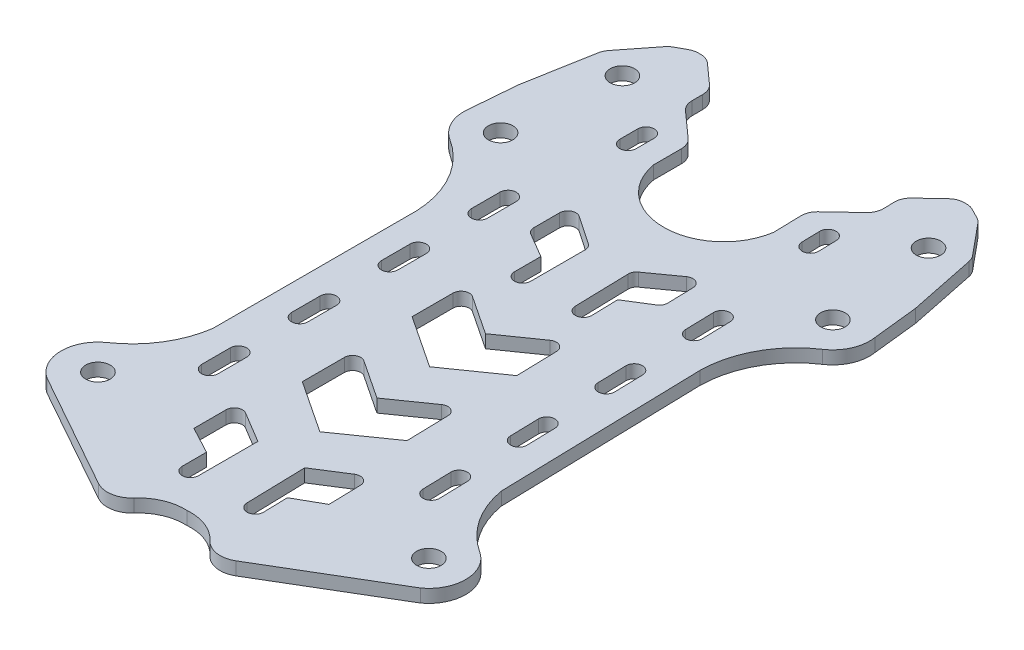
SolidWorks part; units mm, degrees
material "Thornel Mat VMA"
ref_plane "Front Plane" through (0, 0, 0) normal (0, 0, 1) x (1, 0, 0)
ref_plane "Top Plane" through (0, 0, 0) normal (0, 1, 0) x (1, 0, 0)
ref_plane "Right Plane" through (0, 0, 0) normal (1, 0, 0) x (0, 0, -1)
sketch "Sketch1" plane through (0, 0, 0) normal (0, 1, 0) x (1, 0, 0)
  line L0 (480.3423, 413.9052) -> (480.3423, 495.9052) construction
  line L1 (467.9459, 415.8441) -> (453.5897, 423.8818)
  line L2 (458.5115, 439.2435) -> (458.5115, 464.1937)
  line L3 (450.9298, 478.2127) -> (451.3961, 483.794)
  line L4 (451.3961, 483.794) -> (452.8757, 492.0554)
  line L5 (453.2719, 492.9386) -> (456.2786, 496.7643)
  line L6 (456.8868, 497.2807) -> (458.0612, 497.927)
  line L7 (459.0255, 498.1748) -> (459.3166, 498.1748)
  line L8 (460.6508, 497.6647) -> (463.0319, 495.5325)
  line L9 (463.6977, 494.0426) -> (463.6977, 492.7589)
  line L10 (464.3635, 491.2689) -> (467.4781, 488.4799)
  line L11 (468.1439, 486.99) -> (468.1439, 483.5933)
  line L12 (476.2276, 418.3953) -> (475.7559, 455.3953) construction
  line L13 (462.636, 471.2797) -> (462.636, 467.7797) construction
  line L14 (463.636, 471.2797) -> (463.636, 467.7797)
  line L15 (461.636, 471.2797) -> (461.636, 467.7797)
  line L16 (462.636, 460.2797) -> (462.636, 456.7797) construction
  line L19 (462.636, 469.5297) -> (462.636, 436.5297) construction
  line L20 (463.636, 460.2797) -> (463.636, 456.7797)
  line L21 (461.636, 460.2797) -> (461.636, 456.7797)
  line L22 (462.636, 449.2797) -> (462.636, 445.7797) construction
  line L23 (463.636, 449.2797) -> (463.636, 445.7797)
  line L24 (461.636, 449.2797) -> (461.636, 445.7797)
  line L25 (462.636, 438.2797) -> (462.636, 434.7797) construction
  line L28 (463.636, 438.2797) -> (463.636, 434.7797)
  line L29 (461.636, 438.2797) -> (461.636, 434.7797)
  line L30 (475.7559, 455.3953) -> (475.4729, 477.591) construction
  line L31 (472.9659, 463.7324) -> (472.9659, 470.3809)
  line L32 (472.5276, 471.2082) -> (469.0398, 473.5761)
  line L33 (467.4781, 472.7487) -> (467.4781, 469.5911)
  line L34 (467.9703, 468.7297) -> (470.9659, 466.9637)
  line L35 (470.9659, 466.9637) -> (470.9659, 463.7324)
  line L36 (464.3635, 486.4313) -> (464.3635, 484.2313) construction
  line L37 (465.3635, 486.4313) -> (465.3635, 484.2313)
  line L38 (463.3635, 486.4313) -> (463.3635, 484.2313)
  line L39 (475.7559, 455.3953) -> (471.0157, 458.5408)
  line L40 (469.4627, 457.7076) -> (469.4627, 452.706)
  line L41 (469.4627, 452.706) -> (475.8442, 448.4714)
  line L42 (475.9275, 441.9373) -> (471.188, 445.0823)
  line L43 (469.6351, 444.2491) -> (469.6351, 439.1023)
  line L44 (469.6351, 439.1023) -> (476.0176, 434.8669)
  line L45 (473.247, 430.0492) -> (469.4602, 432.3204)
  line L46 (467.9459, 431.4628) -> (467.9459, 427.5216)
  line L47 (467.9459, 427.5216) -> (471.247, 425.7613)
  line L48 (471.247, 425.7613) -> (471.247, 422.7871)
  line L49 (473.247, 430.0492) -> (473.247, 422.7749)
  line L50 (488.5111, 469.8596) -> (489.3525, 436.8703) construction
  line L51 (478.9102, 430.1214) -> (479.0957, 422.8495)
  line L52 (481.0188, 425.8859) -> (481.0946, 422.9127)
  line L53 (484.274, 427.7298) -> (481.0188, 425.8859)
  line L54 (484.1735, 431.6697) -> (484.274, 427.7298)
  line L55 (478.9102, 430.1214) -> (482.6378, 432.4884)
  line L56 (482.2901, 439.2636) -> (476.0176, 434.8669)
  line L57 (482.1589, 444.4088) -> (482.2901, 439.2636)
  line L58 (475.9275, 441.9373) -> (480.5852, 445.2021)
  line L59 (482.1155, 452.8673) -> (475.8442, 448.4714)
  line L60 (481.988, 457.8673) -> (482.1155, 452.8673)
  line L61 (475.7559, 455.3953) -> (480.4143, 458.6607)
  line L62 (480.2493, 467.0821) -> (480.3317, 463.8518)
  line L63 (483.1989, 468.9238) -> (480.2493, 467.0821)
  line L64 (483.5885, 472.9541) -> (483.669, 469.7976)
  line L65 (478.5799, 471.2854) -> (482.0062, 473.7414)
  line L66 (478.3324, 463.8008) -> (478.1628, 470.4471)
  line L67 (482.5598, 487.1738) -> (482.6464, 483.7782)
  line L68 (486.2298, 491.5477) -> (483.1874, 488.6802)
  line L69 (486.8247, 494.3375) -> (486.8574, 493.0542)
  line L70 (489.7783, 498.0361) -> (487.4523, 495.8439)
  line L71 (491.3901, 498.5874) -> (491.099, 498.58)
  line L72 (493.5508, 497.7482) -> (492.3603, 498.3643)
  line L73 (497.2753, 493.4997) -> (494.172, 497.2475)
  line L74 (499.3836, 484.4059) -> (497.6939, 492.6268)
  line L75 (499.992, 478.8383) -> (499.3836, 484.4059)
  line L76 (493.4065, 439.6885) -> (492.7703, 464.6305)
  line L77 (484.5718, 416.0561) -> (498.7183, 424.4572)
  line L78 (486.3532, 486.7117) -> (486.4093, 484.5124) construction
  line L79 (485.3535, 486.6862) -> (485.4096, 484.4869)
  line L80 (487.3529, 486.7372) -> (487.4089, 484.5379)
  line L81 (489.3079, 438.6198) -> (489.3972, 435.1209) construction
  line L82 (488.3082, 438.5943) -> (488.3975, 435.0954)
  line L83 (490.3076, 438.6452) -> (490.3968, 435.1464)
  line L84 (489.0274, 449.6162) -> (489.1167, 446.1173) construction
  line L85 (488.0278, 449.5907) -> (488.117, 446.0918)
  line L86 (490.0271, 449.6417) -> (490.1164, 446.1428)
  line L87 (488.747, 460.6126) -> (488.8362, 457.1137) construction
  line L88 (487.7473, 460.5871) -> (487.8365, 457.0882)
  line L89 (489.7467, 460.6381) -> (489.8359, 457.1392)
  line L90 (488.4665, 471.609) -> (488.5558, 468.1102) construction
  line L91 (487.4668, 471.5835) -> (487.5561, 468.0847)
  line L92 (489.4662, 471.6345) -> (489.5554, 468.1357)
  line L93 (456.799, 491.1108) -> (493.796, 491.5826) construction
  circle A0 centre (455.3894, 477.6108) radius 1.5
  arc A1 (450.9298, 478.2127) -> (452.9867, 473.806) centre (455.3894, 477.6108) ccw
  circle A2 centre (456.1085, 427.6108) radius 1.5
  arc A3 (453.5654, 431.3233) -> (453.5897, 423.8818) centre (456.1085, 427.6108) ccw
  arc A4 (453.5654, 431.3233) -> (458.5115, 439.2435) centre (446.9757, 440.943) ccw
  arc A5 (458.5115, 464.1937) -> (452.9867, 473.806) centre (446.6487, 463.7692) ccw
  arc A6 (468.1439, 483.5933) -> (475.4729, 477.591) centre (475.2975, 484.8524) ccw
  circle A7 centre (456.799, 491.1108) radius 1.5
  arc A8 (476.2276, 418.3953) -> (471.6613, 416.4773) centre (475.9279, 412.7141) ccw
  arc A9 (467.9459, 415.8441) -> (471.6613, 416.4773) centre (469.4114, 418.4617) ccw
  arc A10 (467.4781, 488.4799) -> (468.1439, 486.99) centre (466.1439, 486.99) cw
  arc A11 (463.6977, 492.7589) -> (464.3635, 491.2689) centre (465.6977, 492.7589) ccw
  arc A12 (463.0319, 495.5325) -> (463.6977, 494.0426) centre (461.6977, 494.0426) cw
  arc A13 (459.3166, 498.1748) -> (460.6508, 497.6647) centre (459.3166, 496.1748) cw
  arc A14 (458.0612, 497.927) -> (459.0255, 498.1748) centre (459.0255, 496.1748) cw
  arc A15 (456.2786, 496.7643) -> (456.8868, 497.2807) centre (457.8511, 495.5285) cw
  arc A16 (452.8757, 492.0554) -> (453.2719, 492.9386) centre (454.8444, 491.7028) cw
  arc A17 (463.636, 471.2797) -> (461.636, 471.2797) centre (462.636, 471.2797) ccw
  arc A18 (461.636, 467.7797) -> (463.636, 467.7797) centre (462.636, 467.7797) ccw
  arc A19 (463.636, 460.2797) -> (461.636, 460.2797) centre (462.636, 460.2797) ccw
  arc A20 (461.636, 456.7797) -> (463.636, 456.7797) centre (462.636, 456.7797) ccw
  arc A21 (463.636, 449.2797) -> (461.636, 449.2797) centre (462.636, 449.2797) ccw
  arc A22 (461.636, 445.7797) -> (463.636, 445.7797) centre (462.636, 445.7797) ccw
  arc A25 (463.636, 438.2797) -> (461.636, 438.2797) centre (462.636, 438.2797) ccw
  arc A26 (461.636, 434.7797) -> (463.636, 434.7797) centre (462.636, 434.7797) ccw
  arc A27 (470.9659, 463.7324) -> (472.9659, 463.7324) centre (471.9659, 463.7324) ccw
  arc A28 (469.0398, 473.5761) -> (467.4781, 472.7487) centre (468.4781, 472.7487) ccw
  arc A29 (467.4781, 469.5911) -> (467.9703, 468.7297) centre (468.4781, 469.5911) ccw
  arc A30 (472.9659, 470.3809) -> (472.5276, 471.2082) centre (471.9659, 470.3809) ccw
  arc A31 (465.3635, 486.4313) -> (463.3635, 486.4313) centre (464.3635, 486.4313) ccw
  arc A32 (463.3635, 484.2313) -> (465.3635, 484.2313) centre (464.3635, 484.2313) ccw
  arc A33 (471.0157, 458.5408) -> (469.4627, 457.7076) centre (470.4627, 457.7076) ccw
  arc A34 (471.188, 445.0823) -> (469.6351, 444.2491) centre (470.6351, 444.2491) ccw
  arc A35 (471.247, 422.7871) -> (473.247, 422.7993) centre (472.247, 422.7871) ccw
  arc A36 (469.4602, 432.3204) -> (467.9459, 431.4628) centre (468.9459, 431.4628) ccw
  arc A37 (482.6378, 432.4884) -> (484.1735, 431.6697) centre (483.1739, 431.6442) cw
  arc A38 (481.0946, 422.9127) -> (479.095, 422.8738) centre (480.095, 422.8872) cw
  arc A39 (480.5852, 445.2021) -> (482.1589, 444.4088) centre (481.1592, 444.3833) cw
  arc A40 (480.4143, 458.6607) -> (481.988, 457.8673) centre (480.9883, 457.8418) cw
  arc A41 (478.1628, 470.4471) -> (478.5799, 471.2854) centre (479.1625, 470.4726) cw
  arc A42 (483.669, 469.7976) -> (483.1989, 468.9238) centre (482.6693, 469.7721) cw
  arc A43 (482.0062, 473.7414) -> (483.5885, 472.9541) centre (482.5888, 472.9286) cw
  arc A44 (480.3317, 463.8518) -> (478.3324, 463.8008) centre (479.332, 463.8263) cw
  arc A45 (497.6939, 492.6268) -> (497.2753, 493.4997) centre (495.7348, 492.2242) ccw
  arc A46 (494.172, 497.2475) -> (493.5508, 497.7482) centre (492.6315, 495.9719) ccw
  arc A47 (492.3603, 498.3643) -> (491.3901, 498.5874) centre (491.4411, 496.5881) ccw
  arc A48 (491.099, 498.58) -> (489.7783, 498.0361) centre (491.15, 496.5807) ccw
  arc A49 (487.4523, 495.8439) -> (486.8247, 494.3375) centre (488.8241, 494.3885) ccw
  arc A50 (486.8574, 493.0542) -> (486.2298, 491.5477) centre (484.8581, 493.0032) cw
  arc A51 (483.1874, 488.6802) -> (482.5598, 487.1738) centre (484.5591, 487.2248) ccw
  arc A52 (484.5718, 416.0561) -> (480.8414, 416.5944) centre (483.0399, 418.6355) cw
  arc A53 (476.2276, 418.3953) -> (480.8414, 416.5944) centre (476.6721, 412.7236) cw
  circle A54 centre (493.796, 491.5826) radius 1.5
  arc A55 (482.6464, 483.7782) -> (475.4729, 477.591) centre (475.4631, 484.8545) cw
  arc A56 (492.7703, 464.6305) -> (498.0482, 474.3805) centre (504.6401, 464.5087) cw
  arc A57 (498.5529, 431.8969) -> (493.4065, 439.6885) centre (504.8952, 441.6815) cw
  arc A58 (498.5529, 431.8969) -> (498.7183, 424.4572) centre (496.1053, 428.1208) cw
  circle A59 centre (496.1053, 428.1208) radius 1.5
  arc A60 (499.992, 478.8383) -> (498.0482, 474.3805) centre (495.5493, 478.1229) cw
  circle A61 centre (495.5493, 478.1229) radius 1.5
  arc A62 (485.3535, 486.6862) -> (487.3529, 486.7372) centre (486.3532, 486.7117) cw
  arc A63 (487.4089, 484.5379) -> (485.4096, 484.4869) centre (486.4093, 484.5124) cw
  arc A64 (488.3082, 438.5943) -> (490.3076, 438.6452) centre (489.3079, 438.6198) cw
  arc A65 (490.3968, 435.1464) -> (488.3975, 435.0954) centre (489.3972, 435.1209) cw
  arc A66 (488.0278, 449.5907) -> (490.0271, 449.6417) centre (489.0274, 449.6162) cw
  arc A67 (490.1164, 446.1428) -> (488.117, 446.0918) centre (489.1167, 446.1173) cw
  arc A68 (487.7473, 460.5871) -> (489.7467, 460.6381) centre (488.747, 460.6126) cw
  arc A69 (489.8359, 457.1392) -> (487.8365, 457.0882) centre (488.8362, 457.1137) cw
  arc A70 (487.4668, 471.5835) -> (489.4662, 471.6345) centre (488.4665, 471.609) cw
  arc A71 (489.5554, 468.1357) -> (487.5561, 468.0847) centre (488.5558, 468.1102) cw
  point P9 (475.2975, 491.3467)
  point P26 (462.636, 469.5297)
  point P37 (470.499, 414.4146)
  point P40 (468.1439, 487.8837)
  point P43 (463.6977, 491.8651)
  point P46 (463.6977, 494.9363)
  point P49 (460.0812, 498.1748)
  point P52 (458.5115, 498.1748)
  point P55 (456.5302, 497.0844)
  point P58 (452.9636, 492.5464)
  point P64 (462.636, 458.5297)
  point P76 (462.636, 447.5297)
  point P83 (462.636, 436.5297)
  point P93 (470.9659, 465.3481)
  point P97 (467.4781, 474.6363)
  point P100 (467.4781, 469.0198)
  point P103 (472.9659, 470.9106)
  point P105 (464.3635, 485.3313)
  point P115 (469.4627, 459.5713)
  point P134 (471.247, 424.2742)
  point P137 (467.9459, 433.2286)
  point P217 (484.1285, 433.4349)
  point P218 (481.9405, 459.7304)
  point P221 (486.3812, 485.6121)
  point P226 (478.1493, 470.9767)
  point P227 (483.6835, 469.2264)
  point P228 (483.5403, 474.8411)
  point P231 (489.3525, 436.8703)
  point P238 (489.0721, 447.8667)
  point P245 (488.7916, 458.8632)
  point P250 (497.5934, 493.1155)
  point P251 (493.9124, 497.561)
  point P252 (491.9039, 498.6005)
  point P253 (490.3347, 498.5605)
  point P254 (486.8019, 495.2309)
  point P255 (486.8802, 492.1607)
  point P256 (482.537, 488.0672)
  point P257 (482.0559, 414.562)
  point P260 (488.5111, 469.8596)
  dimension "D5" = 9
  dimension "D6" = 3
  dimension "D8" = 23.3206
  dimension "D11" = 23.7408
  dimension "D29" = 9.3299
  dimension "D31" = 3
  dimension "D32" = 2
  dimension "D34" = 1
  dimension "D37" = 1
  dimension "D27" = 7.2635
  dimension "D43" = 3.4527
  dimension "D44" = 2
  dimension "D50" = 1
  dimension "D51" = 1
  dimension "D52" = 1
  dimension "D54" = 1
  dimension "D59" = 1
  dimension "D60" = 1
  dimension "D64" = 2
  dimension "D71" = 1
  dimension "D1" = 82
  dimension "D2" = 19.3791
  dimension "D3" = 16.9093
  dimension "D4" = 24.9502
  dimension "D9" = 3.1221
  dimension "D10" = 50
  dimension "D12" = 5.5813
  dimension "D13" = 8.8917
  dimension "D14" = 5.7718
  dimension "D15" = 2.2615
  dimension "D16" = 1.5697
  dimension "D17" = 4.8546
  dimension "D18" = 3.0712
  dimension "D19" = 5.9683
  dimension "D20" = 4.2904
  dimension "D21" = 14.0879
  dimension "D22" = 12.7545
  dimension "D23" = 131.843
  dimension "D24" = 185.379
  dimension "D25" = 208.011
  dimension "D26" = 19.9081
  dimension "D28" = 6.8162
  dimension "D30" = 1.7005
  dimension "D33" = 2.5512
  dimension "D35" = 3.5
  dimension "D36" = 3.5
  dimension "D38" = 11
  dimension "D39" = 11
  dimension "D40" = 11
  dimension "D41" = 37
  dimension "D42" = 37
  dimension "D45" = 7.1783
  dimension "D46" = 6.633
  dimension "D47" = 5.6165
  dimension "D48" = 4.0487
  dimension "D49" = 1.3918
  dimension "D53" = 2.2
  dimension "D55" = 1.6586
  dimension "D56" = 55.702
  dimension "D57" = 6.8653
  dimension "D58" = 7.6586
  dimension "D61" = 7.66
  dimension "D62" = 6.5341
  dimension "D63" = 5.1468
  dimension "D65" = 7.2743
  dimension "D66" = 6.1814
  dimension "D67" = 5.707
  dimension "D68" = 3.7412
  dimension "D69" = 2.9743
  dimension "D70" = 1.3122
  dimension "D72" = 4.4068
  dimension "D73" = 63.5
  dimension "D74" = 20
extrude "Boss-Extrude2" add sketch "Sketch1" along normal blind 1.6 contours A60 L75 L74 A45 L73 A46 L72 A47 L71 A48 L70 A49 L69 A50 L68 A51 L67 A55 A6 L11 A10 L10 A11 L9 A12 L8 A13 L7 A14 L6 A15 L5 A16 L4 L3 A1 A5 L2 A4 A3 L1 A9 A8 A53 A52 L77 A58 A57 L76 A56
